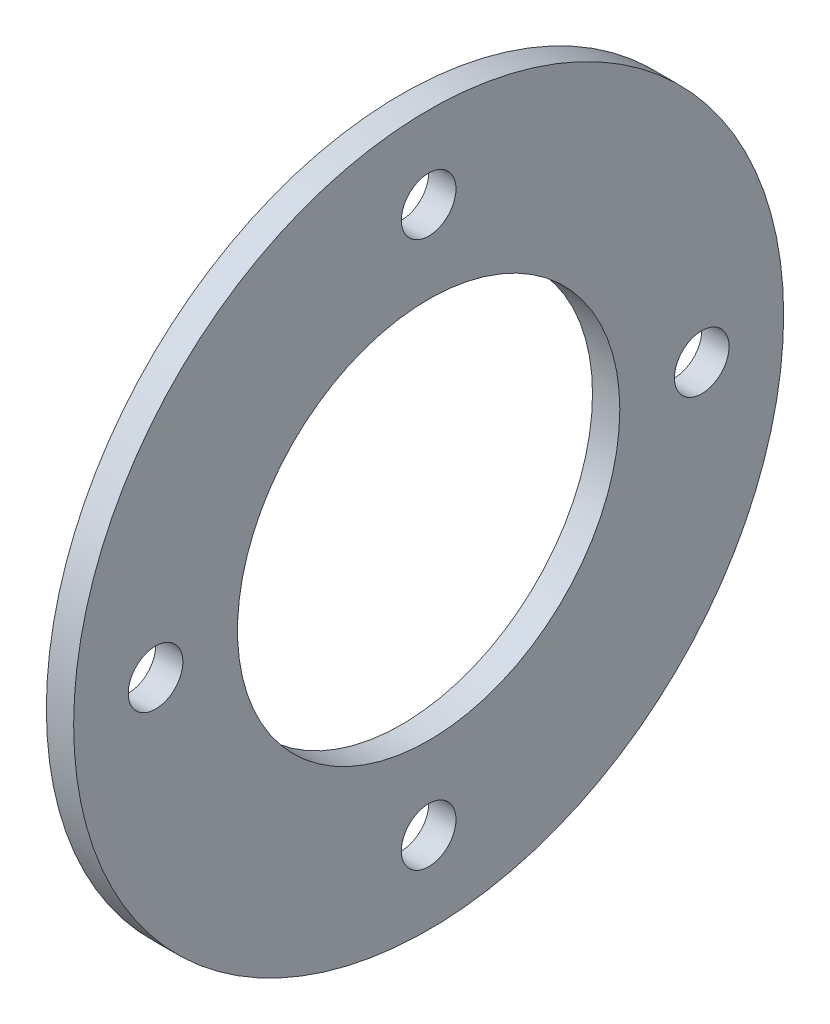
SolidWorks part; units mm, degrees
ref_plane "Front Plane" through (0, 0, 0) normal (0, 0, 1) x (1, 0, 0)
ref_plane "Top Plane" through (0, 0, 0) normal (0, 1, 0) x (1, 0, 0)
ref_plane "Right Plane" through (0, 0, 0) normal (1, 0, 0) x (0, 0, -1)
sketch "Sketch1" plane through (0, 0, 0) normal (1, 0, 0) x (0, 0, -1)
  line L0 (0, 0) -> (0, 20) construction
  circle A0 centre (0, 0) radius 14
  circle A1 centre (0, 0) radius 26
  circle A2 centre (0, 20) radius 2
  circle A3 centre (20, 0) radius 2
  circle A4 centre (0, -20) radius 2
  circle A5 centre (-20, 0) radius 2
  point P15 (0, 0)
  dimension "D2" = 4
  dimension "D3" = 52
  dimension "D4" = 28
  dimension "D1" = 20
  dimension "D5" = 4
extrude "Boss-Extrude1" add sketch "Sketch1" along normal blind 2
